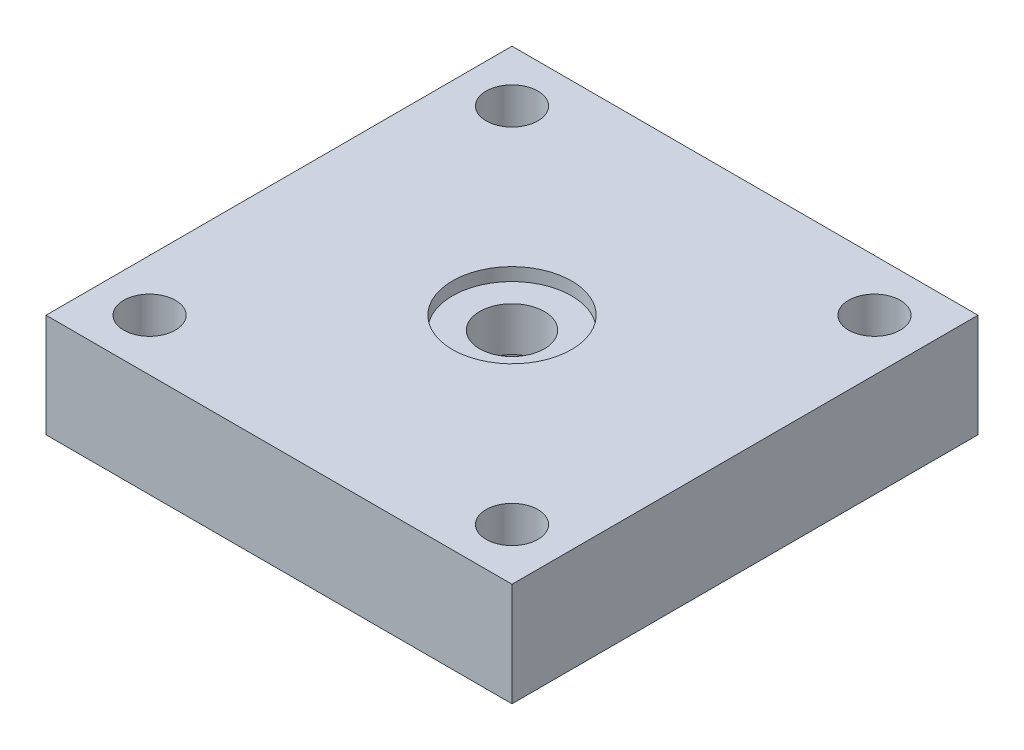
SolidWorks part; units mm, degrees
ref_plane "Front Plane" through (0, 0, 0) normal (0, 0, 1) x (1, 0, 0)
ref_plane "Top Plane" through (0, 0, 0) normal (0, 1, 0) x (1, 0, 0)
ref_plane "Right Plane" through (0, 0, 0) normal (1, 0, 0) x (0, 0, -1)
sketch "Sketch1" plane through (0, 0, 0) normal (0, 1, 0) x (1, 0, 0)
  line L0 (0, 44.3478) -> (0, 0) construction
  line L1 (-90, -90) -> (90, -90)
  line L2 (-90, -90) -> (-90, 90)
  line L3 (-90, 90) -> (90, 90)
  line L4 (90, -90) -> (90, 90)
  line L5 (-90, -90) -> (90, 90) construction
  line L6 (-90, 90) -> (90, -90) construction
  line L7 (0, 0) -> (28.1366, 0) construction
  circle A0 centre (-70, 70) radius 10
  circle A1 centre (70, 70) radius 10
  circle A2 centre (-70, -70) radius 10
  circle A3 centre (70, -70) radius 10
  point P0 (0, 0)
  point P14 (0, 0)
  point P16 (0, 0)
  dimension "D2" = 20
  dimension "D3" = 140
  dimension "D1" = 180
  dimension "D4" = 140
extrude "Boss-Extrude1" add sketch "Sketch1" along normal blind 40
sketch "Sketch2" plane through (0, 40, 0) normal (0, 1, 0) x (1, 0, 0)
  circle A0 centre (0, 0) radius 23
  dimension "D1" = 46
extrude "Cut-Extrude1" cut sketch "Sketch2" against normal blind 5
sketch "Sketch3" plane through (0, 0, 0) normal (0, -1, 0) x (1, 0, 0)
  circle A0 centre (0, 0) radius 25
  dimension "D1" = 50
extrude "Cut-Extrude2" cut sketch "Sketch3" against normal blind 18
sketch "Sketch4" plane through (0, 18, 0) normal (0, -1, 0) x (1, 0, 0)
  circle A0 centre (0, 0) radius 12.5
  dimension "D1" = 25
extrude "Cut-Extrude3" cut sketch "Sketch4" against normal blind 18
